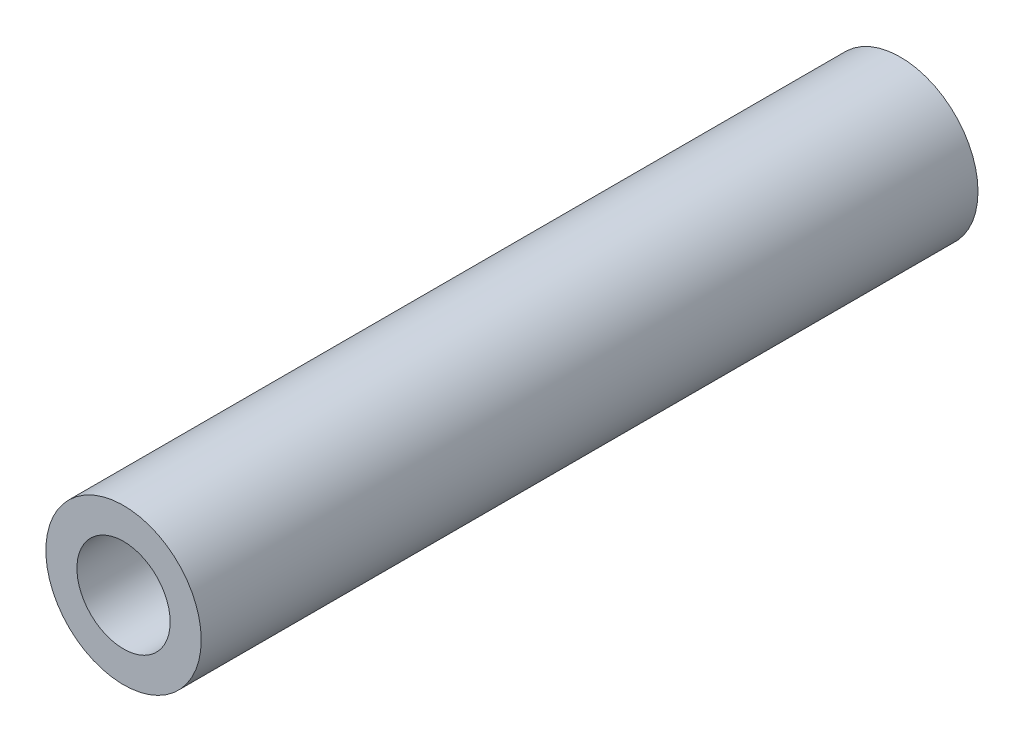
SolidWorks part; units mm, degrees
ref_plane "Alzado" through (0, 0, 0) normal (0, 0, 1) x (1, 0, 0)
ref_plane "Planta" through (0, 0, 0) normal (0, 1, 0) x (1, 0, 0)
ref_plane "Vista lateral" through (0, 0, 0) normal (1, 0, 0) x (0, 0, -1)
sketch "Croquis1" plane through (0, 0, 0) normal (0, 0, 1) x (1, 0, 0)
  circle A0 centre (0, 0) radius 1.5
  circle A1 centre (0, 0) radius 2.5
  dimension "D1" = 3
  dimension "D2" = 5
extrude "Saliente-Extruir1" add sketch "Croquis1" along normal blind 25
